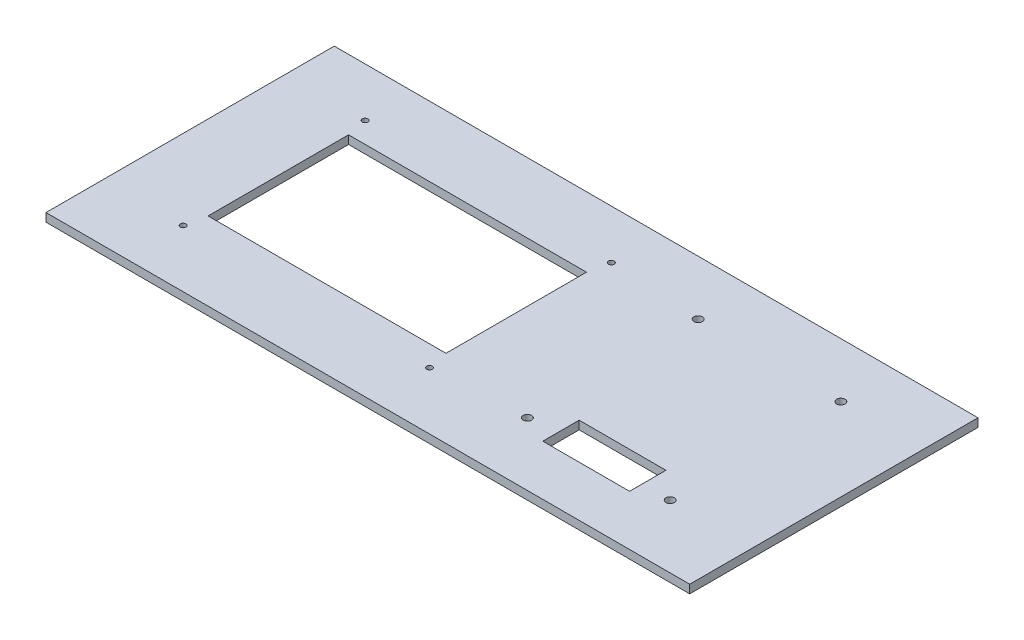
SolidWorks part; units mm, degrees
ref_plane "Front Plane" through (0, 0, 0) normal (0, 0, 1) x (1, 0, 0)
ref_plane "Top Plane" through (0, 0, 0) normal (0, 1, 0) x (1, 0, 0)
ref_plane "Right Plane" through (0, 0, 0) normal (1, 0, 0) x (0, 0, -1)
sketch "Sketch1" plane through (0, 0, 0) normal (0, 1, 0) x (1, 0, 0)
  line L1 (-112.3736, 69.3469) -> (117.6264, 69.3469)
  line L2 (-112.3736, 69.3469) -> (-112.3736, -33.6531)
  line L3 (-112.3736, -33.6531) -> (117.6264, -33.6531)
  line L4 (117.6264, 69.3469) -> (117.6264, -33.6531)
  dimension "D1" = 230
  dimension "D2" = 103
extrude "Boss-Extrude1" add sketch "Sketch1" along normal blind 3
sketch "Sketch2" plane through (0, 3, 0) normal (0, 1, 0) x (1, 0, 0)
  line L0 (117.6264, -33.6531) -> (117.6264, 69.3469) construction
  line L1 (-82.3736, 44.4469) -> (2.6264, 44.4469)
  line L2 (-82.3736, 44.4469) -> (-82.3736, -5.7531)
  line L3 (-82.3736, -5.7531) -> (2.6264, -5.7531)
  line L4 (2.6264, 44.4469) -> (2.6264, -5.7531)
  line L5 (117.6264, 69.3469) -> (-112.3736, 69.3469) construction
  dimension "D1" = 85
  dimension "D2" = 50.2
  dimension "D3" = 115
  dimension "D4" = 24.9
extrude "Cut-Extrude1" cut sketch "Sketch2" against normal blind 3
sketch "Sketch3" plane through (0, 3, 0) normal (0, 1, 0) x (1, 0, 0)
  line L0 (117.6264, -33.6531) -> (117.6264, 69.3469) construction
  line L1 (-112.3736, -33.6531) -> (117.6264, -33.6531) construction
  line L2 (47.1228, -2.6531) -> (78.1264, -2.6531)
  line L3 (47.1228, -2.6531) -> (47.1228, -15.6531)
  line L4 (47.1228, -15.6531) -> (78.1264, -15.6531)
  line L7 (78.1264, -2.6531) -> (78.1264, -15.6531)
  circle A0 centre (37.1264, 49.8469) radius 1.5
  circle A1 centre (88.1264, 49.8469) radius 1.5
  circle A2 centre (88.1264, -11.1531) radius 1.5
  circle A3 centre (37.1264, -11.1531) radius 1.5
  dimension "D5" = 3
  dimension "D6" = 3
  dimension "D2" = 13
  dimension "D3" = 10
  dimension "D4" = 31.0036
  dimension "D7" = 29.5
  dimension "D8" = 29.5
  dimension "D9" = 51
  dimension "D10" = 61
  dimension "D11" = 2
  dimension "D12" = 18
extrude "Cut-Extrude2" cut sketch "Sketch3" against normal blind 3
sketch "Sketch4" plane through (0, 3, 0) normal (0, 1, 0) x (1, 0, 0)
  line L0 (2.6264, 44.4469) -> (-82.3736, 44.4469) construction
  line L1 (-86.3736, 54.3469) -> (6.6264, 54.3469) construction
  line L2 (-86.3736, 54.3469) -> (-86.3736, -15.6531) construction
  line L3 (-86.3736, -15.6531) -> (6.6264, -15.6531) construction
  line L4 (6.6264, 54.3469) -> (6.6264, -15.6531) construction
  line L5 (-82.3736, -5.7531) -> (2.6264, -5.7531) construction
  line L6 (-82.3736, 44.4469) -> (-82.3736, -5.7531) construction
  line L7 (2.6264, -5.7531) -> (2.6264, 44.4469) construction
  circle A0 centre (-83.8736, 51.8469) radius 1
  circle A1 centre (4.1264, 51.8469) radius 1
  circle A2 centre (-83.8736, -13.1531) radius 1
  circle A3 centre (4.1264, -13.1531) radius 1
  dimension "D5" = 2
  dimension "D6" = 2
  dimension "D7" = 2
  dimension "D8" = 2
  dimension "D1" = 9.9
  dimension "D2" = 9.9
  dimension "D3" = 4
  dimension "D4" = 4
  dimension "D9" = 2.5
  dimension "D10" = 2.5
  dimension "D11" = 2.5
  dimension "D12" = 2.5
  dimension "D13" = 2.5
  dimension "D14" = 2.5
  dimension "D15" = 2.5
  dimension "D16" = 2.5
extrude "Cut-Extrude3" cut sketch "Sketch4" against normal blind 3
